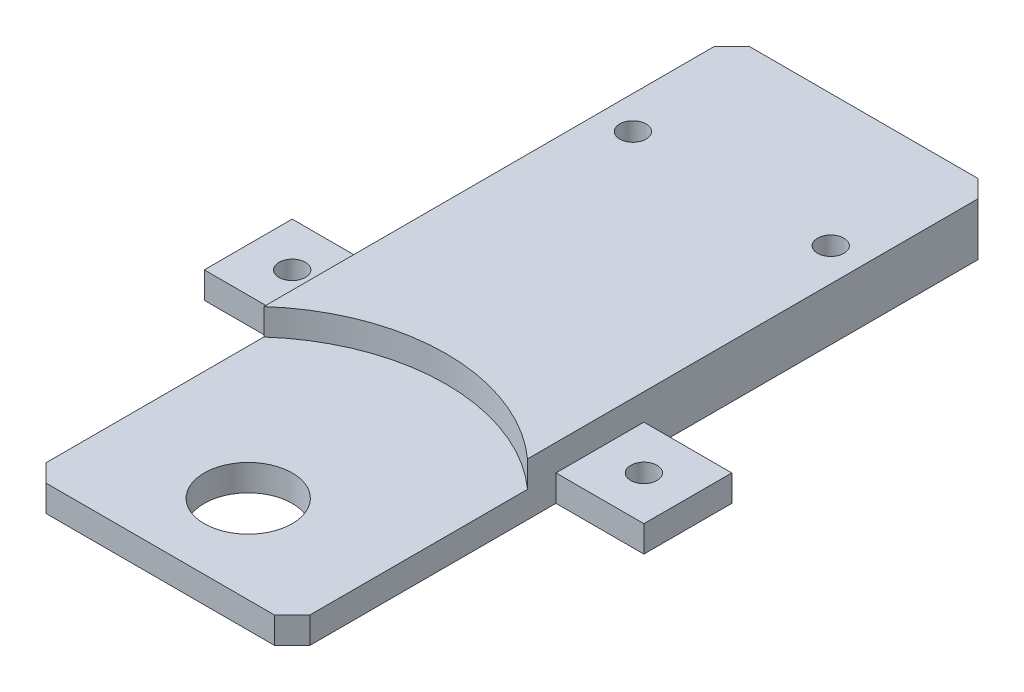
SolidWorks part; units mm, degrees
ref_plane "Front Plane" through (0, 0, 0) normal (0, 0, 1) x (1, 0, 0)
ref_plane "Top Plane" through (0, 0, 0) normal (0, 1, 0) x (1, 0, 0)
ref_plane "Right Plane" through (0, 0, 0) normal (1, 0, 0) x (0, 0, -1)
sketch "Sketch1" plane through (0, 0, 0) normal (0, 1, 0) x (1, 0, 0)
  line L1 (0, 80) -> (30, 80)
  line L2 (0, 80) -> (0, 0)
  line L3 (0, 0) -> (30, 0)
  line L4 (30, 80) -> (30, 0)
  point P4 (0, 0)
  point P6 (0, 0)
  point P7 (0, 0)
  dimension "D1" = 80
  dimension "D2" = 30
extrude "Boss-Extrude1" add sketch "Sketch1" along normal blind 3
sketch "Sketch2" plane through (0, 3, 0) normal (0, 1, 0) x (1, 0, 0)
  line L0 (0, 0) -> (30, 0) construction
  line L1 (30, 0) -> (30, 80) construction
  line L2 (0, 80) -> (30, 80)
  line L3 (0, 80) -> (0, 0)
  line L4 (0, 0) -> (30, 0)
  line L5 (30, 80) -> (30, 0)
  line L6 (15, 80) -> (15, 0) construction
  circle A0 centre (15, 10) radius 20
  circle A1 centre (15, 10) radius 22.5
  point P14 (0, 0)
  line M3 (0, 80) -> (0, 0)
  line M5 (30, 0) -> (30, 80)
  line M6 (30, 80) -> (0, 80)
  dimension "D1" = 40
  dimension "D3" = 45
  dimension "D2" = 10
extrude "Boss-Extrude2" add sketch "Sketch2" along normal blind 3 contours L6 L2 A1 M3 | L6 A1 M6 M5
sketch "Sketch3" plane through (0, 3, 0) normal (0, 1, 0) x (1, 0, 0)
  line L0 (15, 80) -> (15, 0) construction
  line L1 (30, 80) -> (0, 80) construction
  line L2 (0, 0) -> (30, 0) construction
  circle A0 centre (15, 10) radius 5
  point P8 (0, 0)
  point P9 (0, 0)
  dimension "D1" = 10
  dimension "D2" = 10
extrude "Cut-Extrude1" cut sketch "Sketch3" against normal through all
chamfer "Chamfer1" distance 2 angle 45 4 edges at (30, 3, -80) (0, 3, -80) (0, 1.5, 0) (30, 1.5, 0)
sketch "Sketch4" plane through (0, 6, 0) normal (0, 1, 0) x (1, 0, 0)
  line L0 (0, 78) -> (0, 26.7705) construction
  line L1 (0, 70) -> (30, 70)
  line L2 (0, 70) -> (0, 60)
  line L3 (0, 60) -> (30, 60)
  line L4 (30, 70) -> (30, 60)
  line L5 (30, 26.7705) -> (30, 78) construction
  line L6 (28, 80) -> (2, 80) construction
  line L7 (7.5, 70) -> (22.5, 70)
  line L8 (7.5, 70) -> (7.5, 60)
  line L9 (7.5, 60) -> (22.5, 60)
  line L10 (22.5, 70) -> (22.5, 60)
  line L11 (0, 65) -> (30, 65) construction
  line L12 (0, 70) -> (7.5, 60) construction
  line L13 (30, 70) -> (22.5, 60) construction
  circle A0 centre (3.75, 65) radius 1.5
  circle A1 centre (26.25, 65) radius 1.5
  dimension "D5" = 3
  dimension "D1" = 15
  dimension "D2" = 7.5
  dimension "D3" = 10
  dimension "D4" = 10
extrude "Cut-Extrude2" cut sketch "Sketch4" against normal through all contours A1 | A0
sketch "Sketch5" plane through (0, 0, 0) normal (-1, 0, 0) x (0, 0, 1)
  line L0 (16.5, 0) -> (-16.5, 0) construction
  line L1 (-30, 3) -> (-40, 3)
  line L2 (-30, 3) -> (-30, 0)
  line L3 (-30, 0) -> (-40, 0)
  line L4 (-40, 3) -> (-40, 0)
  line L6 (-80, 0) -> (-80, 6) construction
  dimension "D1" = 40
  dimension "D2" = 10
  dimension "D3" = 3
extrude "Boss-Extrude3" add sketch "Sketch5" along normal blind 10
sketch "Sketch6" plane through (0, 6, 0) normal (0, 1, 0) x (1, 0, 0)
  line L0 (0, 35) -> (30, 35) construction
  line L1 (0, 30) -> (0, 40) construction
  line L2 (30, 26.7705) -> (30, 78) construction
  line L3 (-10, 40) -> (0, 30) construction
  line L4 (-10, 30) -> (0, 40) construction
  point P6 (15, 35)
  point P17 (-5, 35)
hole_wizard "Ø3.0mm Dowel Hole1" positions "Sketch6" profile "Sketch7" hole size "Ø3.0" standard "ISO"
sketch "Sketch7" plane through (-5, 6, -35) normal (1, 0, 0) x (0, 0, 1)
  line L0 (0, 0) -> (0, 6)
  line L1 (0, 6) -> (1.5, 6)
  line L2 (1.5, 6) -> (1.5, 0.025)
  line L3 (1.5, 0.025) -> (1.525, 0)
  line L5 (1.525, 0) -> (0, 0)
  line L6 (-1.5, 0.025) -> (-1.525, 0) construction
  line L11 (0, -6.35) -> (0, 107.95) construction
  dimension "Thru Hole Dia." = 3
  dimension "Thru Hole Depth" = 6
  dimension "Near C'Sink Dia." = 3.05
  dimension "Near C'Sink Angle" = 90
ref_plane "Plane1" through (15, 0, 0) normal (-1, 0, 0) x (0, 0, 1)
mirror "Mirror1" about plane through (15, 0, 0) normal (-1, 0, 0) of "Ø3.0mm Dowel Hole1", "Boss-Extrude3"
